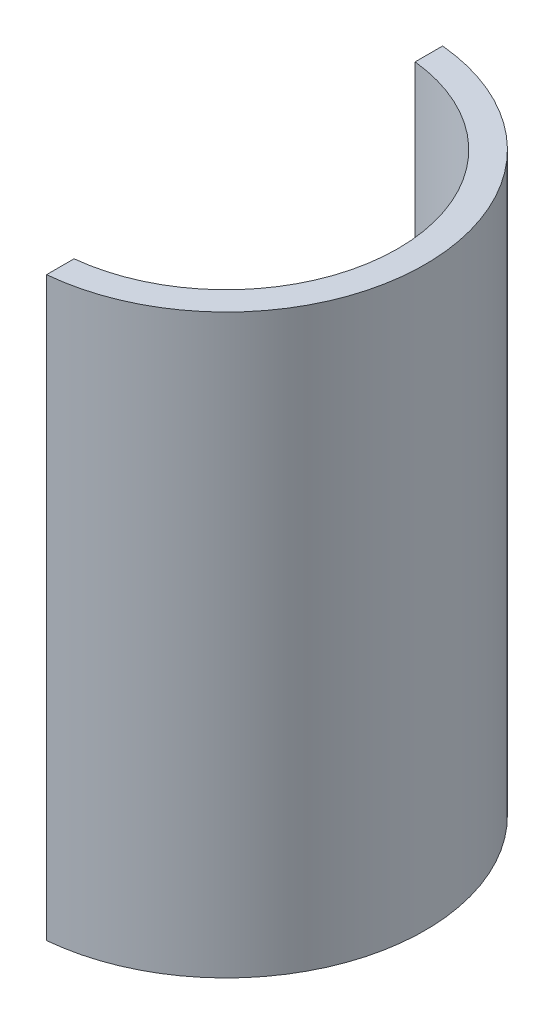
SolidWorks part; units mm, degrees
ref_plane "Front Plane" through (0, 0, 0) normal (0, 0, 1) x (1, 0, 0)
ref_plane "Top Plane" through (0, 0, 0) normal (0, 1, 0) x (1, 0, 0)
ref_plane "Right Plane" through (0, 0, 0) normal (1, 0, 0) x (0, 0, -1)
sketch "Sketch1" plane through (0, 0, 0) normal (0, 1, 0) x (1, 0, 0)
  circle A0 centre (0, 0) radius 34.5
  circle A1 centre (0, 0) radius 40
  dimension "D1" = 69
  dimension "D2" = 80
extrude "Boss-Extrude1" add sketch "Sketch1" along normal blind 116
sketch "Sketch2" plane through (0, 116, 0) normal (0, 1, 0) x (1, 0, 0)
  line L2 (3.6962, 39.8289) -> (3.6962, -39.8289)
  circle A0 centre (0, 0) radius 40 construction
  arc A3 (3.6962, 39.8289) -> (3.6962, -39.8289) centre (0, 0) ccw
extrude "Cut-Extrude1" cut sketch "Sketch2" against normal blind 123
